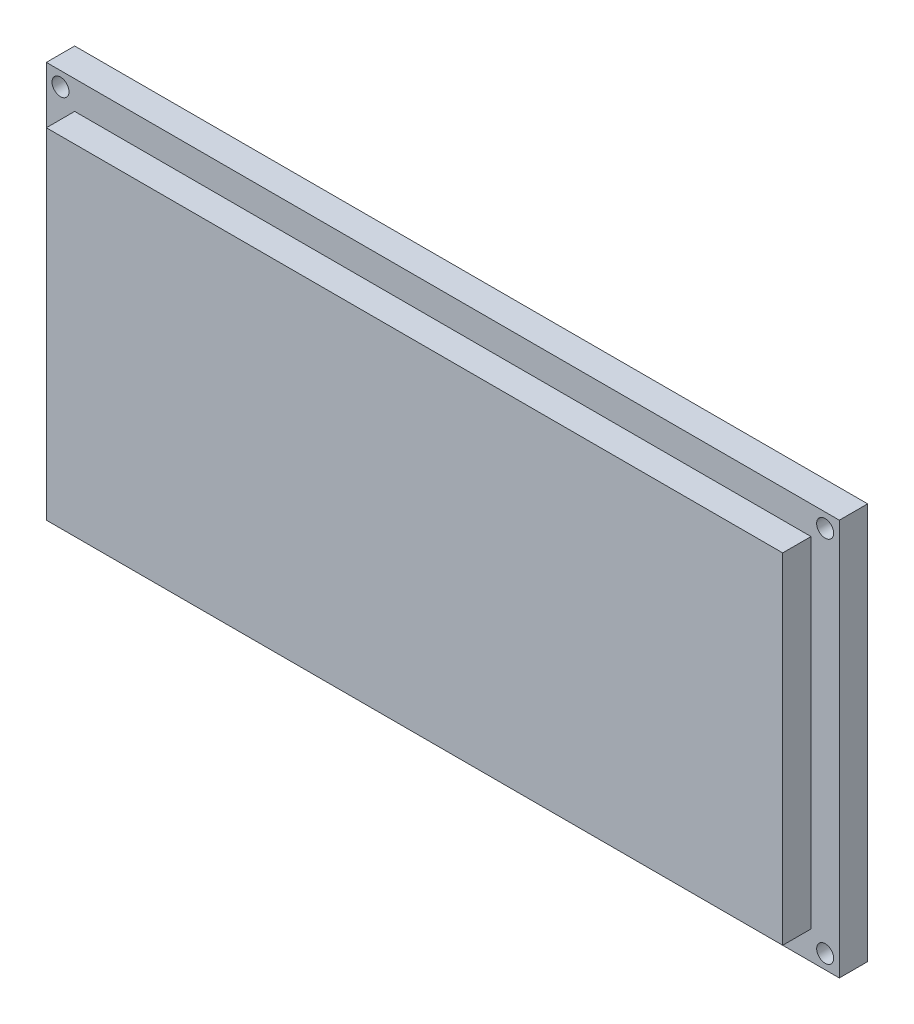
SolidWorks part; units mm, degrees
material "PC High Viscosity"
ref_plane "Front Plane" through (0, 0, 0) normal (0, 0, 1) x (1, 0, 0)
ref_plane "Top Plane" through (0, 0, 0) normal (0, 1, 0) x (1, 0, 0)
ref_plane "Right Plane" through (0, 0, 0) normal (1, 0, 0) x (0, 0, -1)
sketch "Sketch1" plane through (0, 0, 0) normal (0, 0, 1) x (1, 0, 0)
  line L1 (0, 0) -> (140, 0)
  line L2 (0, 0) -> (0, 70)
  line L3 (0, 70) -> (140, 70)
  line L4 (140, 0) -> (140, 70)
extrude "Boss-Extrude1" add sketch "Sketch1" along normal blind 5
sketch "Sketch2" plane through (0, 0, 5) normal (0, 0, 1) x (1, 0, 0)
  line L0 (0, 0) -> (0, 5)
  line L1 (0, 70) -> (0, 0) construction
  line L2 (0, 5) -> (5, 5)
  line L4 (5, 5) -> (135, 5)
  line L5 (5, 5) -> (5, 65)
  line L6 (5, 65) -> (135, 65)
  line L7 (135, 5) -> (135, 65)
extrude "Boss-Extrude2" add sketch "Sketch2" along normal blind 5 contours L4 L7 L6 L5
sketch "Sketch3" plane through (0, 0, 0) normal (0, 0, -1) x (-1, 0, 0)
  line L0 (-140, 0) -> (-140, 2.5)
  line L1 (-140, 0) -> (-140, 70) construction
  line L2 (-140, 2.5) -> (-137.5, 2.5)
  line L4 (-137.5, 2.5) -> (-2.5, 2.5)
  line L5 (-137.5, 2.5) -> (-137.5, 67.5)
  line L6 (-137.5, 67.5) -> (-2.5, 67.5)
  line L7 (-2.5, 2.5) -> (-2.5, 67.5)
hole_wizard "M3 Clearance Hole1" positions "3DSketch1" profile "Sketch5" hole size "M3" standard "ANSI Metric" end condition through all
sketch3d "3DSketch1"
  point P0 (137.5, 2.5, 0)
  point P3 (137.5, 67.5, 0)
  point P6 (2.5, 2.5, 0)
  point P9 (2.5, 67.5, 0)
sketch "Sketch5" plane through (137.5, 2.5, 0) normal (1, 0, 0) x (0, 1, 0)
  line L0 (0, 0) -> (0, 10)
  line L1 (0, 10) -> (1.5, 10)
  line L2 (1.5, 10) -> (1.5, 0)
  line L5 (1.5, 0) -> (0, 0)
  line L11 (0, -6.35) -> (0, 107.95) construction
  dimension "Thru Hole Dia." = 3
  dimension "Thru Hole Depth" = 10
